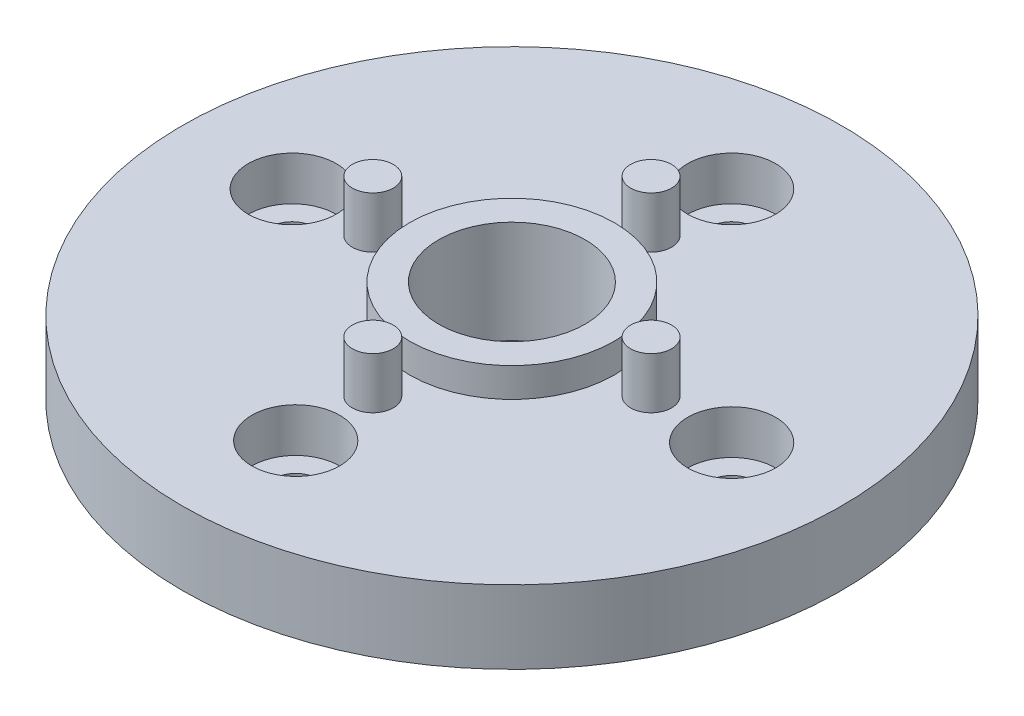
SolidWorks part; units mm, degrees
ref_plane "前视基准面" through (0, 0, 0) normal (0, 0, 1) x (1, 0, 0)
ref_plane "上视基准面" through (0, 0, 0) normal (0, 1, 0) x (1, 0, 0)
ref_plane "右视基准面" through (0, 0, 0) normal (1, 0, 0) x (0, 0, -1)
other "Configuration Table"
sketch "草图1" plane through (0, 0, 0) normal (0, 1, 0) x (1, 0, 0)
  circle A0 centre (0, 0) radius 22.5
extrude "凸台-拉伸2" add sketch "草图1" against normal blind 5
sketch "草图5" plane through (0, 0, 0) normal (0, 1, 0) x (1, 0, 0)
  circle A1 centre (0, 15) radius 1.5
  circle A2 centre (15, 0) radius 1.5
  circle A4 centre (0, -14.7602) radius 1.5
  circle A5 centre (-15, 0) radius 1.5
extrude "切除-拉伸2" cut sketch "草图5" against normal blind 11
sketch "草图6" plane through (0, 0, 0) normal (0, 1, 0) x (1, 0, 0)
  circle A0 centre (0, 15) radius 3
  circle A2 centre (15, 0) radius 3
  circle A3 centre (0, -14.7602) radius 3
  circle A4 centre (-15, 0) radius 3
extrude "切除-拉伸3" cut sketch "草图6" against normal blind 3
sketch "草图9" plane through (0, 0, 0) normal (0, 1, 0) x (1, 0, 0)
  circle A0 centre (0, 9.5) radius 1.4
  circle A1 centre (9.5, 0) radius 1.4
  circle A2 centre (0, -9.5) radius 1.4
  circle A3 centre (-9.5, 0) radius 1.4
  point P2 (0, 0)
  point P3 (0, 0)
  point P5 (-0.3981, 0.1837)
  dimension "D1" = 9.5
  dimension "D2" = 9.5
  dimension "D3" = 9.5
  dimension "D4" = 9.5
extrude "凸台-拉伸5" add sketch "草图9" along normal blind 3.5
sketch "草图10" plane through (0, 0, 0) normal (0, 1, 0) x (1, 0, 0)
  circle A0 centre (0, 0) radius 7
extrude "凸台-拉伸6" add sketch "草图10" along normal blind 2
sketch "草图11" plane through (0, 0, 0) normal (0, 1, 0) x (1, 0, 0)
  circle A0 centre (0, 0) radius 5
extrude "切除-拉伸4" cut sketch "草图11" against normal blind 14 and the other way blind 14
